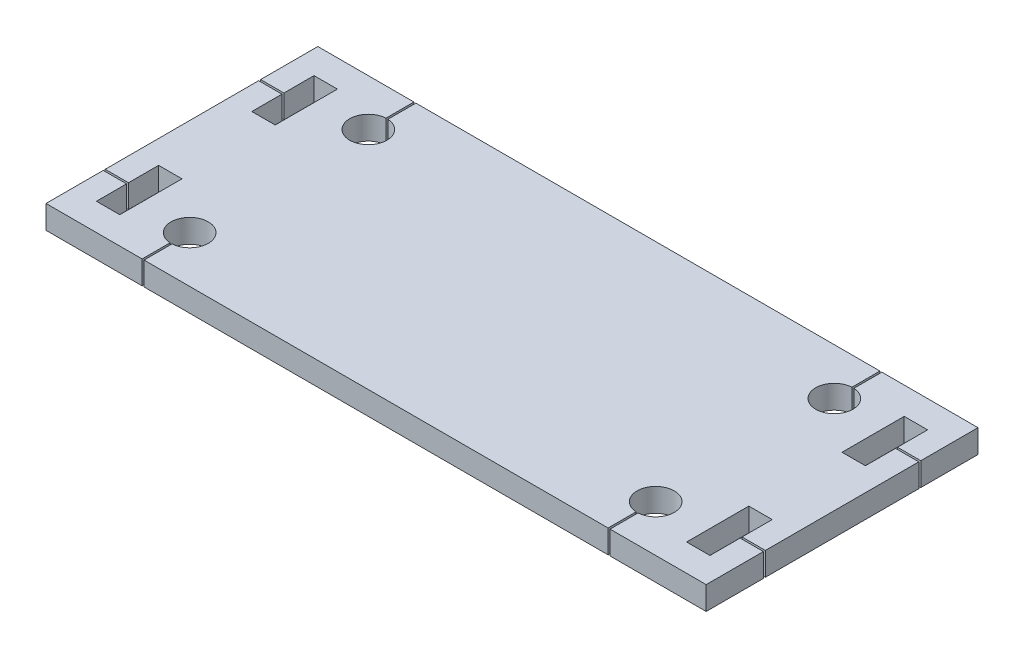
SolidWorks part; units mm, degrees
material "Chapa F.F 1020 - 2 mm"
ref_plane "Plano frontal" through (0, 0, 0) normal (0, 0, 1) x (1, 0, 0)
ref_plane "Plano superior" through (0, 0, 0) normal (0, 1, 0) x (1, 0, 0)
ref_plane "Plano direito" through (0, 0, 0) normal (1, 0, 0) x (0, 0, -1)
sketch "Esboço2" plane through (0, 0, 0) normal (0, 1, 0) x (1, 0, 0)
  line L1 (42.5, 17.5) -> (-42.5, 17.5)
  line L2 (42.5, 17.5) -> (42.5, -17.5)
  line L3 (42.5, -17.5) -> (-42.5, -17.5)
  line L4 (-42.5, 17.5) -> (-42.5, -17.5)
  line L5 (42.5, 17.5) -> (-42.5, -17.5) construction
  line L6 (42.5, -17.5) -> (-42.5, 17.5) construction
  point P0 (0, 0)
  dimension "D1" = 85
  dimension "D2" = 35
extrude "Ressalto-extrusão2" add sketch "Esboço2" along normal blind 3
sketch "Esboço4" plane through (0, 0, 0) normal (0, -1, 0) x (-1, 0, 0)
  line L1 (30, 11.5) -> (-30, 11.5) construction
  line L2 (30, 11.5) -> (30, -11.5) construction
  line L3 (30, -11.5) -> (-30, -11.5) construction
  line L4 (-30, 11.5) -> (-30, -11.5) construction
  line L5 (30, 11.5) -> (-30, -11.5) construction
  line L6 (30, -11.5) -> (-30, 11.5) construction
  point P0 (0, 0)
  dimension "D1" = 60
  dimension "D2" = 23
hole_wizard "Furo com folga de M41" positions "Esboço8" profile "Esboço9" hole size "M4" standard "Din" end condition through all
sketch "Esboço8" plane through (0, 0, 0) normal (0, -1, 0) x (-1, 0, 0)
  point P0 (30, -11.5)
  point P3 (30, 11.5)
  point P6 (-30, 11.5)
  point P9 (-30, -11.5)
sketch "Esboço9" plane through (-30, 0, 11.5) normal (1, 0, 0) x (0, 0, -1)
  line L0 (0, 0) -> (0, 3)
  line L1 (0, 3) -> (2.4, 3)
  line L2 (2.4, 3) -> (2.4, 0)
  line L5 (2.4, 0) -> (0, 0)
  line L11 (0, -6.35) -> (0, 107.95) construction
  dimension "Thru Hole Dia." = 4.8
  dimension "Thru Hole Depth" = 3
sketch "Esboço10" plane through (0, 3, 0) normal (0, 1, 0) x (1, 0, 0)
  line L0 (0, 0) -> (-42.5, 0) construction
  line L1 (-36.49, 14.01) -> (-39.5, 14.01)
  line L2 (-36.49, 14.01) -> (-36.49, 6)
  line L3 (-36.49, 6) -> (-39.5, 6)
  line L4 (-39.5, 14.01) -> (-39.5, 6)
  line L5 (0, 0) -> (0, 17.5) construction
  line L6 (42.5, 17.5) -> (-42.5, 17.5) construction
  line L7 (-42.5, 17.5) -> (-42.5, -17.5) construction
  line L8 (-39.5, -14.01) -> (-39.5, -6)
  line L9 (-36.49, -6) -> (-39.5, -6)
  line L10 (-36.49, -14.01) -> (-36.49, -6)
  line L11 (-36.49, -14.01) -> (-39.5, -14.01)
  line L12 (36.49, -14.01) -> (39.5, -14.01)
  line L13 (36.49, -14.01) -> (36.49, -6)
  line L14 (36.49, -6) -> (39.5, -6)
  line L15 (39.5, -14.01) -> (39.5, -6)
  line L16 (39.5, 14.01) -> (39.5, 6)
  line L17 (36.49, 6) -> (39.5, 6)
  line L18 (36.49, 14.01) -> (36.49, 6)
  line L19 (36.49, 14.01) -> (39.5, 14.01)
  dimension "D1" = 8.01
  dimension "D2" = 3.01
  dimension "D3" = 12
  dimension "D4" = 79
extrude "Corte-extrusão2" cut sketch "Esboço10" against normal blind 10
sketch "Esboço11" plane through (0, 3, 0) normal (0, 1, 0) x (1, 0, 0)
  line L0 (0, 0) -> (0, 17.5) construction
  line L1 (42.5, 17.5) -> (-42.5, 17.5) construction
  line L2 (0, 0) -> (-42.5, 0) construction
  line L3 (-42.5, 17.5) -> (-42.5, -17.5) construction
  line L4 (-39.5, 10.13) -> (-42.5, 10.13)
  line L5 (-39.5, 14.01) -> (-39.5, 6) construction
  line L6 (-39.5, 9.88) -> (-42.5, 9.88)
  line L7 (-39.5, 10.005) -> (-42.5, 10.005) construction
  line L8 (-39.5, 10.13) -> (-39.5, 9.88)
  line L9 (-42.5, 10.13) -> (-42.5, 9.88)
  line L10 (-29.875, 17.5) -> (-29.875, 13.8967)
  line L11 (-30.125, 17.5) -> (-30.125, 13.8967)
  line L12 (-30, 11.5) -> (-30, 17.5) construction
  line L13 (-29.875, 17.5) -> (-30.125, 17.5)
  line L14 (-29.875, 13.8967) -> (-30.125, 13.8967)
  line L15 (-30, -11.5) -> (-30, -17.5) construction
  line L16 (-39.5, -10.005) -> (-42.5, -10.005) construction
  line L17 (-29.875, -13.8967) -> (-30.125, -13.8967)
  line L18 (-29.875, -17.5) -> (-30.125, -17.5)
  line L19 (-30.125, -17.5) -> (-30.125, -13.8967)
  line L20 (-29.875, -17.5) -> (-29.875, -13.8967)
  line L21 (-42.5, -10.13) -> (-42.5, -9.88)
  line L22 (-39.5, -10.13) -> (-39.5, -9.88)
  line L23 (-39.5, -9.88) -> (-42.5, -9.88)
  line L24 (-39.5, -10.13) -> (-42.5, -10.13)
  line L25 (39.5, -10.005) -> (42.5, -10.005) construction
  line L26 (30, -11.5) -> (30, -17.5) construction
  line L27 (39.5, -10.13) -> (42.5, -10.13)
  line L28 (39.5, -9.88) -> (42.5, -9.88)
  line L29 (39.5, -10.13) -> (39.5, -9.88)
  line L30 (42.5, -10.13) -> (42.5, -9.88)
  line L31 (29.875, -17.5) -> (29.875, -13.8967)
  line L32 (30.125, -17.5) -> (30.125, -13.8967)
  line L33 (29.875, -17.5) -> (30.125, -17.5)
  line L34 (29.875, -13.8967) -> (30.125, -13.8967)
  line L35 (30, 11.5) -> (30, 17.5) construction
  line L36 (39.5, 10.005) -> (42.5, 10.005) construction
  line L37 (29.875, 13.8967) -> (30.125, 13.8967)
  line L38 (29.875, 17.5) -> (30.125, 17.5)
  line L39 (30.125, 17.5) -> (30.125, 13.8967)
  line L40 (29.875, 17.5) -> (29.875, 13.8967)
  line L41 (42.5, 10.13) -> (42.5, 9.88)
  line L42 (39.5, 10.13) -> (39.5, 9.88)
  line L43 (39.5, 9.88) -> (42.5, 9.88)
  line L44 (39.5, 10.13) -> (42.5, 10.13)
  circle A0 centre (-30, 11.5) radius 2.4 construction
  dimension "D1" = 0.25
  dimension "D2" = 0.25
extrude "Corte-extrusão3" cut sketch "Esboço11" against normal through all
